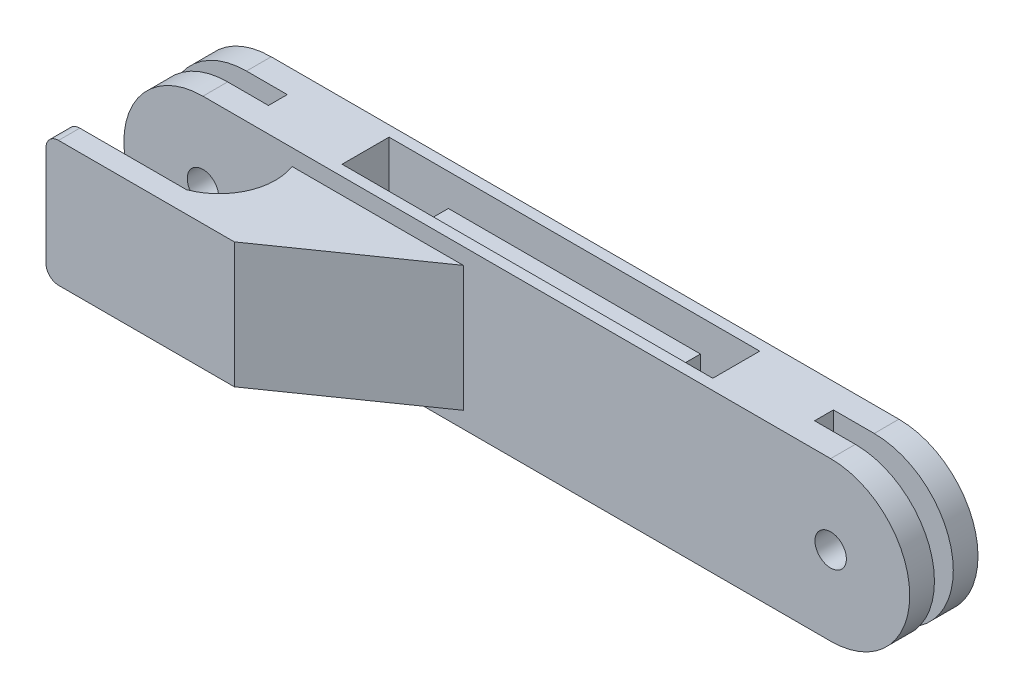
SolidWorks part; units mm, degrees
ref_plane "Front" through (0, 0, 0) normal (0, 0, 1) x (1, 0, 0)
ref_plane "Top" through (0, 0, 0) normal (0, 1, 0) x (1, 0, 0)
ref_plane "Right" through (0, 0, 0) normal (1, 0, 0) x (0, 0, -1)
sketch "Sketch1" plane through (0, 0, 0) normal (0, 0, 1) x (1, 0, 0)
  line L0 (-47.2174, -8.0761) -> (79.7826, -8.0761) construction
  line L1 (-47.2174, 7.9239) -> (79.7826, 7.9239)
  line L2 (-47.2174, -24.0761) -> (79.7826, -24.0761)
  arc A0 (-47.2174, 7.9239) -> (-47.2174, -24.0761) centre (-47.2174, -8.0761) ccw
  arc A1 (79.7826, -24.0761) -> (79.7826, 7.9239) centre (79.7826, -8.0761) ccw
  circle A2 centre (-47.2174, -8.0761) radius 3.175
  circle A3 centre (79.7826, -8.0761) radius 3.175
  point P2 (16.2826, -8.0761)
  dimension "D1" = 16
  dimension "D3" = 6.35
  dimension "D4" = 6.35
  dimension "D2" = 127
extrude "Boss-Extrude1" add sketch "Sketch1" along normal blind 5
sketch "Sketch2" plane through (0, 0, 5) normal (0, 0, 1) x (1, 0, 0)
  line L2 (-38.9624, -7.0761) -> (-38.9624, 7.9239)
  line L4 (79.7826, 7.9239) -> (-47.2174, 7.9239) construction
  line L9 (71.5276, -7.0761) -> (71.5276, 7.9239)
  line L10 (-38.9624, 7.9239) -> (71.5276, 7.9239)
  line L11 (-38.9624, -7.0761) -> (71.5276, -7.0761)
  point P13 (-38.9624, 0.4239)
  point P16 (16.9972, 0.4239)
  point P24 (71.5276, 0.4239)
extrude "Boss-Extrude2" add sketch "Sketch2" along normal blind 3.81
sketch "Sketch5" plane through (0, 0, 8.81) normal (0, 0, 1) x (1, 0, 0)
  line L0 (-47.2174, -8.0761) -> (79.7826, -8.0761) construction
  line L1 (-47.2174, 7.9239) -> (79.7826, 7.9239)
  line L2 (-47.2174, -24.0761) -> (79.7826, -24.0761)
  arc A0 (-47.2174, 7.9239) -> (-47.2174, -24.0761) centre (-47.2174, -8.0761) ccw
  arc A1 (79.7826, -24.0761) -> (79.7826, 7.9239) centre (79.7826, -8.0761) ccw
  circle A2 centre (-47.2174, -8.0761) radius 3.175
  circle A3 centre (79.7826, -8.0761) radius 3.175
  point P4 (16.2826, -8.0761)
  dimension "D1" = 16
  dimension "D2" = 6.35
  dimension "D3" = 6.35
extrude "Boss-Extrude3" add sketch "Sketch5" along normal blind 5
sketch "Sketch6" plane through (0, 7.9239, 0) normal (0, 1, 0) x (1, 0, 0)
  line L0 (16.2826, 0) -> (16.2826, -13.81)
  line L1 (79.7826, 0) -> (-47.2174, 0) construction
  line L2 (79.7826, -13.81) -> (-47.2174, -13.81) construction
  line L3 (-38.9624, -6.905) -> (71.5276, -6.905)
  line L4 (-38.9624, -8.81) -> (-38.9624, -5) construction
  line L5 (71.5276, -8.81) -> (71.5276, -5) construction
  line L7 (-21.2174, -11.655) -> (53.7826, -11.655)
  line L8 (-21.2174, -11.655) -> (-21.2174, -2.155)
  line L9 (-21.2174, -2.155) -> (53.7826, -2.155)
  line L10 (53.7826, -11.655) -> (53.7826, -2.155)
  line L11 (-21.2174, -11.655) -> (53.7826, -2.155) construction
  line L12 (-21.2174, -2.155) -> (53.7826, -11.655) construction
  point P12 (16.2826, -6.905)
extrude "Cut-Extrude1" cut sketch "Sketch6" against normal blind 6.5 contours L7 L10 L9 L8
sketch "Sketch7" plane through (0, 1.4239, 0) normal (0, 1, 0) x (1, 0, 0)
  line L0 (-21.2174, -11.655) -> (53.7826, -11.655) construction
  line L1 (-21.2174, -2.155) -> (-9.2174, -2.155)
  line L2 (-21.2174, -2.155) -> (-21.2174, -11.655)
  line L3 (-21.2174, -11.655) -> (-9.2174, -11.655)
  line L4 (-9.2174, -2.155) -> (-9.2174, -11.655)
  line L6 (53.7826, -2.155) -> (41.7826, -2.155)
  line L7 (53.7826, -2.155) -> (53.7826, -11.655)
  line L8 (53.7826, -11.655) -> (41.7826, -11.655)
  line L9 (41.7826, -2.155) -> (41.7826, -11.655)
  point P12 (0, 0)
  point P13 (0, 0)
extrude "Cut-Extrude2" cut sketch "Sketch7" against normal blind 30.48 contours L4 L3 L2 L1 | L7 L6 L9 L8
sketch "Sketch10" plane through (0, 0, 13.81) normal (0, 0, 1) x (1, 0, 0)
  line L0 (-47.2174, -24.0761) -> (79.7826, -24.0761) construction
  line L1 (-34.5174, -20.7761) -> (-57.3774, -20.7761)
  line L3 (-34.5174, 4.6239) -> (-57.3774, 4.6239)
  line L4 (-59.9174, -18.2361) -> (-59.9174, 2.0839)
  line L5 (-34.5174, -20.7761) -> (-59.9174, 4.6239) construction
  line L6 (-34.5174, 4.6239) -> (-59.9174, -20.7761) construction
  line L7 (-34.5174, 4.6239) -> (-21.8174, 4.6239)
  line L9 (-34.5174, -20.7761) -> (-21.8174, -20.7761)
  line L10 (-21.8174, 4.6239) -> (-21.8174, -20.7761)
  arc A1 (-57.3774, -20.7761) -> (-59.9174, -18.2361) centre (-57.3774, -18.2361) cw
  arc A2 (-57.3774, 4.6239) -> (-59.9174, 2.0839) centre (-57.3774, 2.0839) ccw
  point P15 (0, 0)
  dimension "D1" = 2.54
  dimension "D2" = 35.56
  dimension "D3" = 25.4
  dimension "D4" = 12.7
  dimension "D5" = 3.3
extrude "Boss-Extrude4" add sketch "Sketch10" along normal blind 19.05 contours L4 A2 L3 L7 L10 L9 L1 A1
sketch "Sketch14" plane through (0, 4.6239, 0) normal (0, 1, 0) x (1, 0, 0)
  line L0 (-59.9174, -13.81) -> (-29.1834, -13.81)
  line L1 (-56.9493, -13.81) -> (-21.8174, -13.81) construction
  line L2 (-59.9174, -13.81) -> (-59.9174, -28.5602)
  line L3 (-59.9174, -32.86) -> (-59.9174, -13.81) construction
  line L4 (-59.9174, -28.5602) -> (-35.7956, -28.5602)
  arc A0 (-29.1834, -13.81) -> (-35.7956, -28.5602) centre (-39.8646, -17.879) cw
  dimension "D1" = 11.43
  dimension "D2" = 24.1218
  dimension "D3" = 14.7502
  dimension "D4" = 30.734
extrude "Cut-Extrude3" cut sketch "Sketch14" against normal blind 30.48
sketch "Sketch15" plane through (0, -20.7761, 0) normal (0, -1, 0) x (1, 0, 0)
  line L0 (-21.8174, 13.81) -> (5.4637, 13.81)
  line L1 (-47.2174, 13.81) -> (79.7826, 13.81) construction
  line L2 (-21.8174, 32.86) -> (5.4637, 13.81)
  line L3 (-21.8174, 32.86) -> (-21.8174, 13.81)
extrude "Boss-Extrude5" add sketch "Sketch15" against normal blind 25.4
